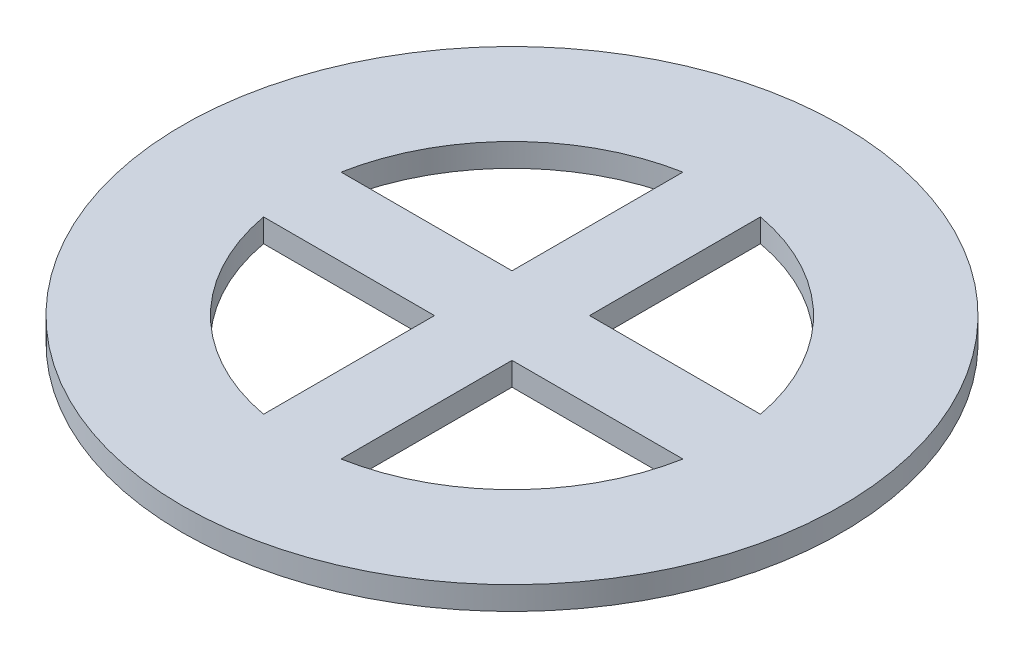
SolidWorks part; units mm, degrees
ref_plane "Plano frontal" through (0, 0, 0) normal (0, 0, 1) x (1, 0, 0)
ref_plane "Plano superior" through (0, 0, 0) normal (0, 1, 0) x (1, 0, 0)
ref_plane "Plano direito" through (0, 0, 0) normal (1, 0, 0) x (0, 0, -1)
sketch "Esboço1" plane through (0, 0, 0) normal (0, 1, 0) x (1, 0, 0)
  line L0 (0, 0) -> (-55, 0) construction
  line L1 (-55, 0) -> (55, 0) construction
  line L2 (-55, -10) -> (55, -10)
  line L3 (-55, 10) -> (55, 10)
  line L4 (0, 0) -> (0, 55) construction
  line L5 (0, 55) -> (0, -55) construction
  line L6 (-10, 55) -> (-10, -55)
  line L7 (10, 55) -> (10, -55)
  circle A0 centre (0, 0) radius 85
  circle A1 centre (0, 0) radius 55
  dimension "D1" = 30
  dimension "D2" = 10
  dimension "D4" = 10
  dimension "D3" = 10
  dimension "D5" = 10
extrude "Ressalto-extrusão1" add sketch "Esboço1" along normal blind 6
